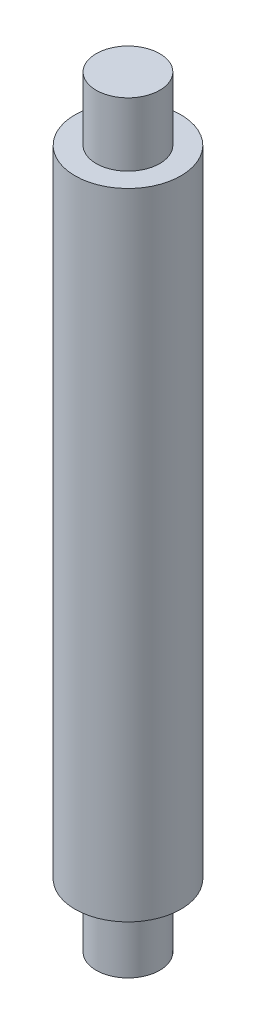
SolidWorks part; units mm, degrees
ref_plane "前视基准面" through (0, 0, 0) normal (0, 0, 1) x (1, 0, 0)
ref_plane "上视基准面" through (0, 0, 0) normal (0, 1, 0) x (1, 0, 0)
ref_plane "右视基准面" through (0, 0, 0) normal (1, 0, 0) x (0, 0, -1)
other "Configuration Table"
sketch "草图1" plane through (0, 0, 0) normal (0, 1, 0) x (1, 0, 0)
  circle A0 centre (0, 0) radius 2.5
  dimension "D1" = 5
extrude "凸台-拉伸2" add sketch "草图1" against normal mid plane 30
sketch "草图2" plane through (0, 15, 0) normal (0, 1, 0) x (1, 0, 0)
  circle A0 centre (0, 0) radius 1.5
  dimension "D1" = 3
extrude "凸台-拉伸3" add sketch "草图2" along normal blind 3
sketch "草图3" plane through (0, -15, 0) normal (0, -1, 0) x (1, 0, 0)
  circle A0 centre (0, 0) radius 1.5
  dimension "D1" = 3
extrude "凸台-拉伸4" add sketch "草图3" along normal blind 3
